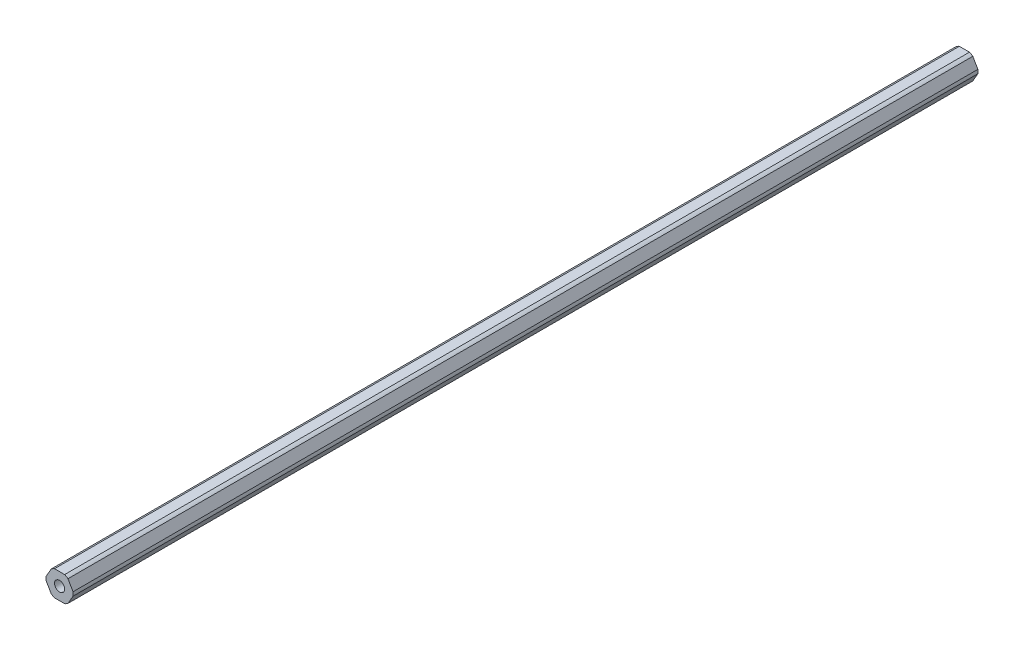
SolidWorks part; units mm, degrees
ref_plane "Front Plane" through (0, 0, 0) normal (0, 0, 1) x (1, 0, 0)
ref_plane "Top Plane" through (0, 0, 0) normal (0, 1, 0) x (1, 0, 0)
ref_plane "Right Plane" through (0, 0, 0) normal (1, 0, 0) x (0, 0, -1)
ref_plane "Plane1" through (0, 0, 228.6) normal (0, 0, 1) x (1, 0, 0)
sketch "Sketch1" plane through (0, 0, 228.6) normal (0, 0, 1) x (1, 0, 0)
  line L0 (4.2415, -5.4043) -> (6.801, -0.9711)
  line L1 (6.801, 0.9711) -> (4.2415, 5.4043)
  line L2 (2.5595, 6.3754) -> (-2.5595, 6.3754)
  line L3 (-4.2415, 5.4043) -> (-6.801, 0.9711)
  line L4 (-6.801, -0.9711) -> (-4.2415, -5.4043)
  line L5 (-2.5595, -6.3754) -> (2.5595, -6.3754)
  arc A0 (6.801, -0.9711) -> (6.801, 0.9711) centre (0, 0) ccw
  arc A1 (4.2415, 5.4043) -> (2.5595, 6.3754) centre (0, 0) ccw
  arc A2 (-2.5595, 6.3754) -> (-4.2415, 5.4043) centre (0, 0) ccw
  arc A3 (-6.801, 0.9711) -> (-6.801, -0.9711) centre (0, 0) ccw
  arc A4 (-4.2415, -5.4043) -> (-2.5595, -6.3754) centre (0, 0) ccw
  arc A5 (2.5595, -6.3754) -> (4.2415, -5.4043) centre (0, 0) ccw
  circle A6 centre (0, 0) radius 2.55
extrude "Boss-Extrude1" add sketch "Sketch1" against normal blind 457.2
